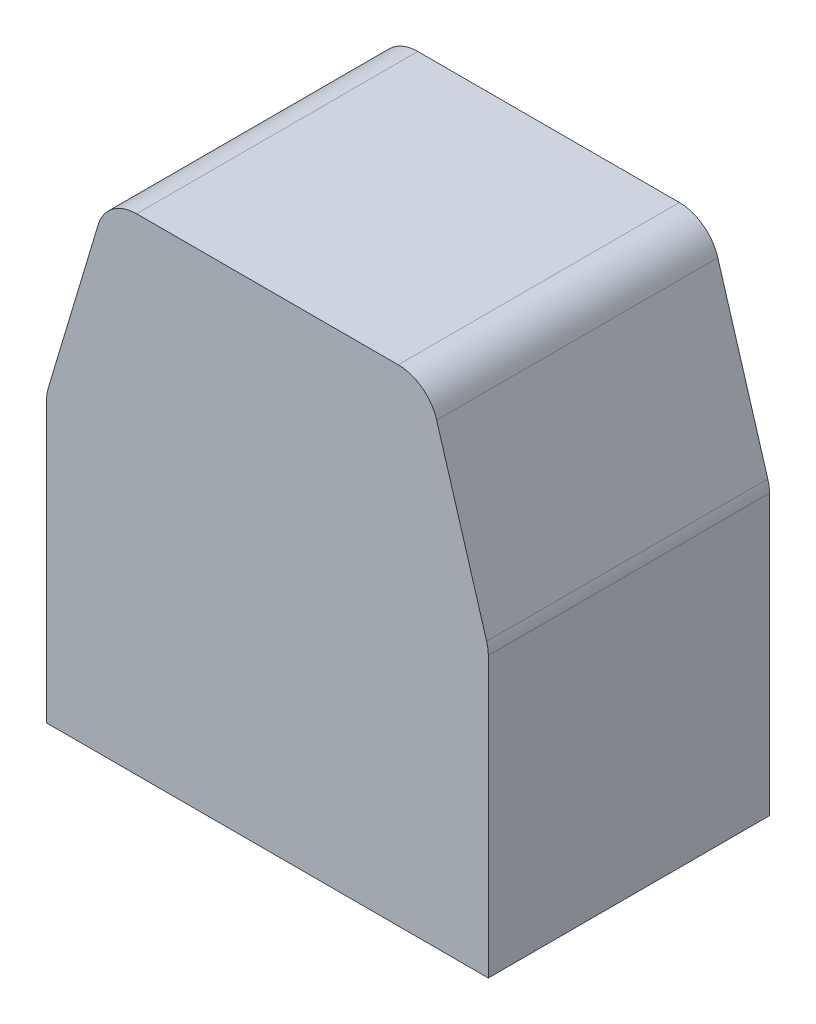
SolidWorks part; units mm, degrees
ref_plane "前视基准面" through (0, 0, 0) normal (0, 0, 1) x (1, 0, 0)
ref_plane "上视基准面" through (0, 0, 0) normal (0, 1, 0) x (1, 0, 0)
ref_plane "右视基准面" through (0, 0, 0) normal (1, 0, 0) x (0, 0, -1)
sketch "草图1" plane through (0, 0, 0) normal (0, 0, 1) x (1, 0, 0)
  line L0 (-50, -30.5) -> (-52.5981, -29)
  line L2 (-55, 34.0323) -> (-55, -35.5)
  line L3 (-55, -35.5) -> (55, -35.5)
  line L4 (55, 34.0323) -> (55, -35.5)
  line L5 (-55, 35.5) -> (55, -35.5) construction
  line L6 (-55, -35.5) -> (55, 35.5) construction
  line L7 (0, 35.5) -> (0, 85.5) construction
  line L10 (-54.5783, 36.9058) -> (-42.138, 78.3735)
  line L11 (-32.5597, 85.5) -> (0, 85.5)
  line L12 (0, 85.5) -> (32.5597, 85.5)
  line L13 (42.138, 78.3735) -> (54.5783, 36.9058)
  line L14 (-50, -35.5) -> (50, -35.5)
  line L20 (0, 35.5) -> (0, -35.5) construction
  line L23 (-50, 35.5) -> (-38.638, 73.3735)
  line L25 (38.638, 73.3735) -> (50, 35.5)
  line L26 (-50, 35.5) -> (-50, -30.5)
  line L27 (50, 35.5) -> (50, -30.5)
  line L29 (-29.0597, 80.5) -> (0, 80.5)
  line L30 (0, 80.5) -> (29.0597, 80.5)
  line L31 (-52.5981, -29) -> (-52.5981, -34)
  line L32 (-52.5981, -34) -> (-50, -32.5)
  line L33 (50, -30.5) -> (52.5981, -29)
  line L34 (52.5981, -29) -> (52.5981, -34)
  line L35 (52.5981, -34) -> (50, -32.5)
  line L36 (50, -32.2727) -> (50, -35.5)
  line L37 (-50, -32.2727) -> (-50, -35.5)
  arc A0 (55, 34.0323) -> (54.5783, 36.9058) centre (45, 34.0323) ccw
  arc A1 (42.138, 78.3735) -> (32.5597, 85.5) centre (32.5597, 75.5) ccw
  arc A2 (-32.5597, 85.5) -> (-42.138, 78.3735) centre (-32.5597, 75.5) ccw
  arc A3 (-54.5783, 36.9058) -> (-55, 34.0323) centre (-45, 34.0323) ccw
  arc A4 (38.638, 73.3735) -> (29.0597, 80.5) centre (29.0597, 70.5) ccw
  arc A5 (-29.0597, 80.5) -> (-38.638, 73.3735) centre (-29.0597, 70.5) ccw
  point P0 (0, 0)
  point P25 (40, 85.5)
  point P28 (-40, 85.5)
  dimension "D7" = 10
  dimension "D20" = 10
  dimension "D1" = 110
  dimension "D2" = 5
  dimension "D3" = 50
  dimension "D4" = 40
  dimension "D5" = 71
  dimension "D6" = 40
  dimension "D8" = 120
  dimension "D9" = 120
  dimension "D10" = 5
  dimension "D11" = 1.5
  dimension "D12" = 120
  dimension "D13" = 120
  dimension "D14" = 5
  dimension "D15" = 1.5
  dimension "D16" = 2
  dimension "D17" = 2
  dimension "D18" = 5
  dimension "D19" = 5
extrude "凸台-拉伸4" add sketch "草图1" along normal blind 70 contours A5 L29 L30 A4 L25 L27 L33 L34 L35 L36 L3 L4 A0 L13 A1 L12 L11 A2 L10 A3 L2 L37 L32 L31 L0 L26 L23
sketch "草图2" plane through (0, 0, 70) normal (0, 0, 1) x (1, 0, 0)
  line L0 (-50, -35.5) -> (50, -35.5)
  line L21 (-29.0597, 80.5) -> (29.0597, 80.5)
  line L22 (38.638, 73.3735) -> (50, 35.5)
  line L23 (50, 35.5) -> (50, -30.5)
  line L24 (50, -30.5) -> (52.5981, -29)
  line L25 (52.5981, -29) -> (52.5981, -34)
  line L26 (52.5981, -34) -> (50, -32.5)
  line L27 (50, -32.5) -> (50, -35.5)
  line L28 (50, -35.5) -> (55, -35.5)
  line L29 (55, -35.5) -> (55, 34.0323)
  line L30 (54.5783, 36.9058) -> (42.138, 78.3735)
  line L31 (32.5597, 85.5) -> (-32.5597, 85.5)
  line L32 (-42.138, 78.3735) -> (-54.5783, 36.9058)
  line L33 (-55, 34.0323) -> (-55, -35.5)
  line L34 (-55, -35.5) -> (-50, -35.5)
  line L35 (-50, -35.5) -> (-50, -32.5)
  line L36 (-50, -32.5) -> (-52.5981, -34)
  line L37 (-52.5981, -34) -> (-52.5981, -29)
  line L38 (-52.5981, -29) -> (-50, -30.5)
  line L39 (-50, -30.5) -> (-50, 35.5)
  line L40 (-50, 35.5) -> (-38.638, 73.3735)
  line L41 (-29.0597, 80.5) -> (29.0597, 80.5)
  line L42 (38.638, 73.3735) -> (50, 35.5)
  line L43 (50, 35.5) -> (50, -30.5)
  line L44 (50, -30.5) -> (52.5981, -29)
  line L45 (52.5981, -29) -> (52.5981, -34)
  line L46 (52.5981, -34) -> (50, -32.5)
  line L47 (50, -32.5) -> (50, -35.5)
  line L55 (-50, -35.5) -> (-50, -32.5)
  line L56 (-50, -32.5) -> (-52.5981, -34)
  line L57 (-52.5981, -34) -> (-52.5981, -29)
  line L58 (-52.5981, -29) -> (-50, -30.5)
  line L59 (-50, -30.5) -> (-50, 35.5)
  line L60 (-50, 35.5) -> (-38.638, 73.3735)
  arc A6 (-29.0597, 80.5) -> (-38.638, 73.3735) centre (-29.0597, 70.5) ccw
  arc A7 (38.638, 73.3735) -> (29.0597, 80.5) centre (29.0597, 70.5) ccw
  arc A8 (55, 34.0323) -> (54.5783, 36.9058) centre (45, 34.0323) ccw
  arc A9 (42.138, 78.3735) -> (32.5597, 85.5) centre (32.5597, 75.5) ccw
  arc A10 (-32.5597, 85.5) -> (-42.138, 78.3735) centre (-32.5597, 75.5) ccw
  arc A11 (-54.5783, 36.9058) -> (-55, 34.0323) centre (-45, 34.0323) ccw
  arc A12 (-29.0597, 80.5) -> (-38.638, 73.3735) centre (-29.0597, 70.5) ccw
  arc A13 (38.638, 73.3735) -> (29.0597, 80.5) centre (29.0597, 70.5) ccw
  dimension "D1" = 0
extrude "凸台-拉伸5" add sketch "草图2" against normal blind 5
